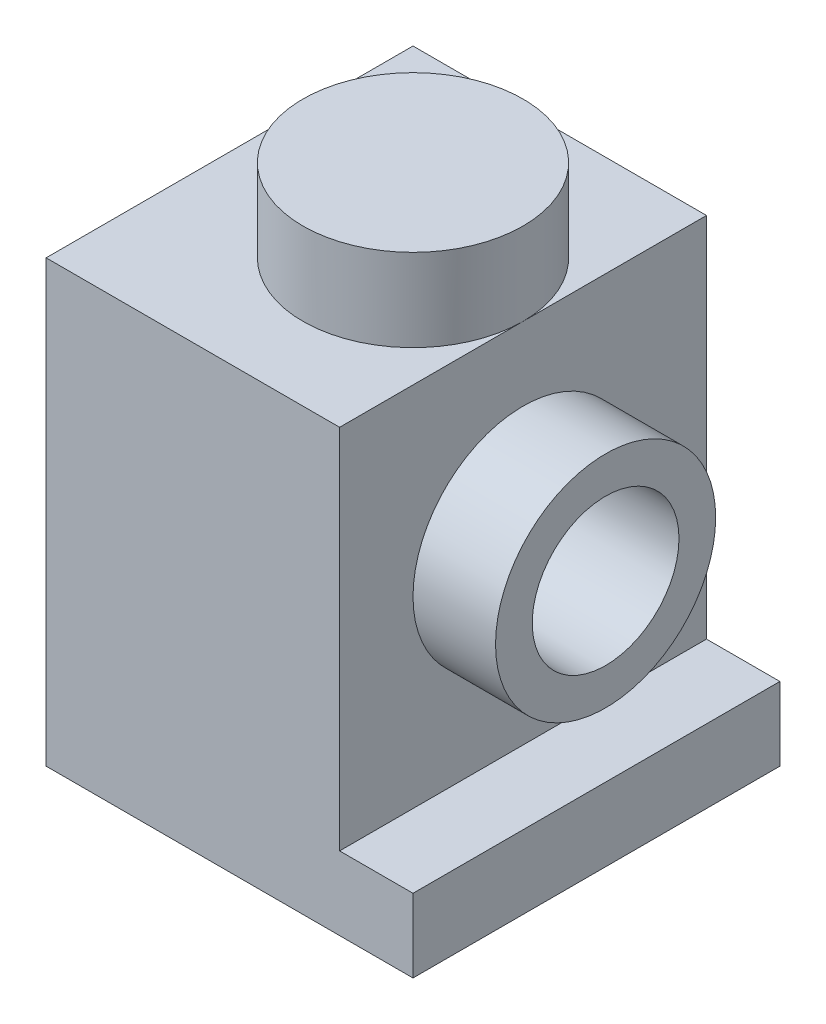
SolidWorks part; units mm, degrees
ref_plane "Спереди" through (0, 0, 0) normal (0, 0, 1) x (1, 0, 0)
ref_plane "Сверху" through (0, 0, 0) normal (0, 1, 0) x (1, 0, 0)
ref_plane "Справа" through (0, 0, 0) normal (1, 0, 0) x (0, 0, -1)
sketch "Эскиз1" plane through (0, 0, 0) normal (0, 1, 0) x (1, 0, 0)
  line L1 (4, -4) -> (-4, -4)
  line L2 (4, -4) -> (4, 4)
  line L3 (4, 4) -> (-4, 4)
  line L4 (-4, -4) -> (-4, 4)
  line L5 (4, -4) -> (-4, 4) construction
  line L6 (4, 4) -> (-4, -4) construction
  point P0 (0, 0)
  dimension "D1" = 8
  dimension "D2" = 8
extrude "Бобышка-Вытянуть1" add sketch "Эскиз1" along normal blind 9.6
sketch "Эскиз2" plane through (0, 9.6, 0) normal (0, 1, 0) x (1, 0, 0)
  line L0 (4, 4) -> (-4, 4) construction
  line L1 (2.4, 4) -> (4, 4)
  line L2 (2.4, 4) -> (2.4, -4)
  line L3 (2.4, -4) -> (4, -4)
  line L4 (4, 4) -> (4, -4)
  dimension "D1" = 1.6
extrude "Вырез-Вытянуть1" cut sketch "Эскиз2" against normal blind 8
sketch "Эскиз5" plane through (2.4, 0, 0) normal (1, 0, 0) x (0, 0, -1)
  line L0 (-4, 9.6) -> (4, 1.6)
  line L1 (4, 1.6) -> (-4, 1.6) construction
  line L2 (4, 9.6) -> (-4, 1.6)
  circle A0 centre (0, 5.6) radius 2.4
  circle A1 centre (0, 5.6) radius 1.6
  point P12 (0, 0)
extrude "Бобышка-Вытянуть2" add sketch "Эскиз5" along normal blind 1.8 contours A0
sketch "Эскиз8" plane through (4.2, 0, 0) normal (1, 0, 0) x (0, 0, -1)
  circle A0 centre (0, 5.6) radius 1.6
extrude "Вырез-Вытянуть3" cut sketch "Эскиз8" against normal blind 9
sketch "Эскиз9" plane through (0, 9.6, 0) normal (0, 1, 0) x (1, 0, 0)
  line L0 (-4, 4) -> (-4, -4) construction
  circle A1 centre (0, 0) radius 2.4
  point P16 (0, 0)
  dimension "D1" = 4
extrude "Бобышка-Вытянуть3" add sketch "Эскиз9" along normal blind 1.8
sketch "Эскиз10" plane through (-4, 0, 0) normal (-1, 0, 0) x (0, 0, 1)
  line L0 (2.4, 9.6) -> (2.4, 0)
  line L1 (-4, 0) -> (4, 0) construction
  line L2 (-2.4, 9.6) -> (-2.4, 0)
sketch "Эскиз11" plane through (-4, 0, 0) normal (-1, 0, 0) x (0, 0, 1)
  circle A0 centre (0, 5.6) radius 2.4
sketch "Эскиз13" plane through (-4, 0, 0) normal (-1, 0, 0) x (0, 0, 1)
  line L0 (-2.4, 9.6) -> (-2.4, 0) construction
  line L1 (2.4, 3.1983) -> (-2.4, 3.1983)
  line L2 (2.4, 3.1983) -> (2.4, 8.0017)
  line L3 (2.4, 8.0017) -> (-2.4, 8.0017)
  line L4 (-2.4, 3.1983) -> (-2.4, 8.0017)
  line L5 (2.4, 3.1983) -> (-2.4, 8.0017) construction
  line L6 (2.4, 8.0017) -> (-2.4, 3.1983) construction
  point P0 (0, 5.6)
extrude "Вырез-Вытянуть4" cut sketch "Эскиз13" against normal blind 5
sketch "Эскиз14" plane through (0, 0, 0) normal (0, -1, 0) x (1, 0, 0)
  line L1 (2.8813, -2.6885) -> (-2.8813, -2.6885)
  line L2 (2.8813, -2.6885) -> (2.8813, 2.6885)
  line L3 (2.8813, 2.6885) -> (-2.8813, 2.6885)
  line L4 (-2.8813, -2.6885) -> (-2.8813, 2.6885)
  line L5 (2.8813, -2.6885) -> (-2.8813, 2.6885) construction
  line L6 (2.8813, 2.6885) -> (-2.8813, -2.6885) construction
  point P0 (0, 0)
